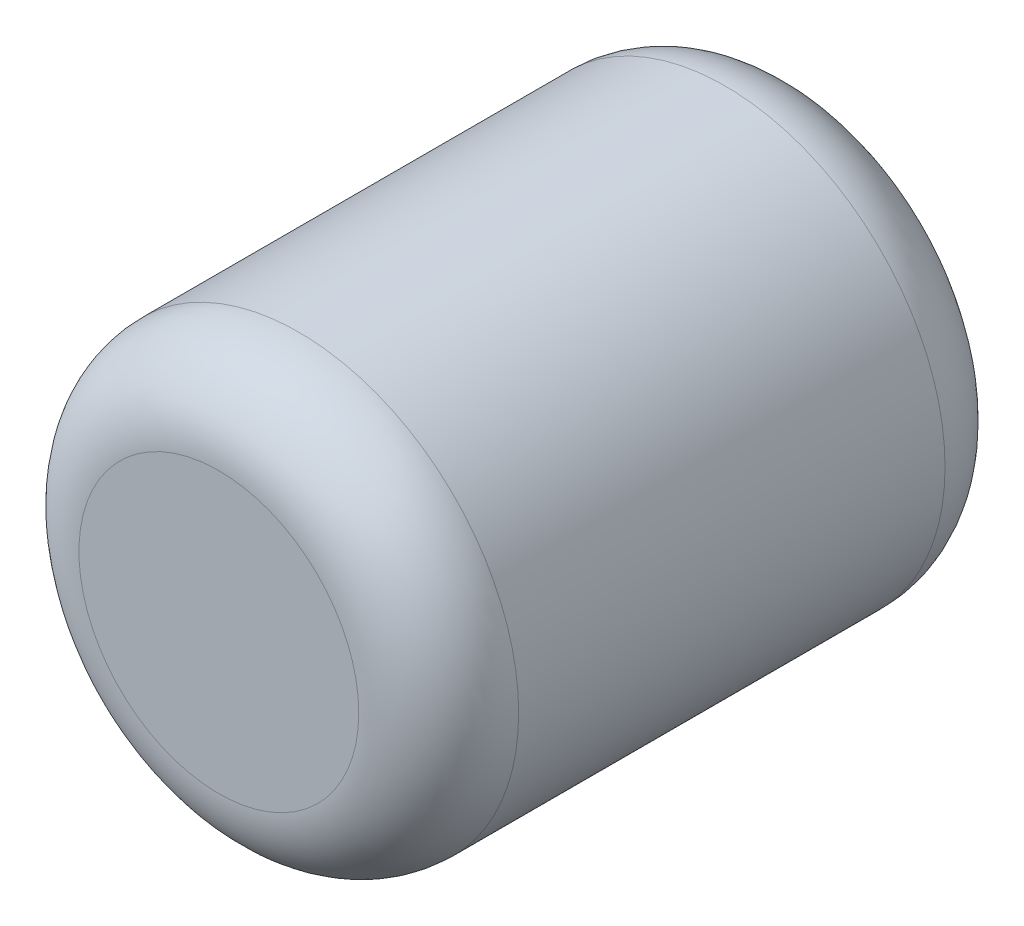
SolidWorks part; units mm, degrees
ref_plane "Front Plane" through (0, 0, 0) normal (0, 0, 1) x (1, 0, 0)
ref_plane "Top Plane" through (0, 0, 0) normal (0, 1, 0) x (1, 0, 0)
ref_plane "Right Plane" through (0, 0, 0) normal (1, 0, 0) x (0, 0, -1)
sketch "Sketch2" plane through (0, 0, 0) normal (0, 0, 1) x (1, 0, 0)
  circle A0 centre (0, 0) radius 8.25
  dimension "D1" = 16.5
extrude "Boss-Extrude1" add sketch "Sketch2" along normal blind 22
ref_point "Point1"
ref_point "Point2"
fillet "Fillet1" radius 3 2 edges at (8.25, 0, 22) (8.25, 0, 0)
